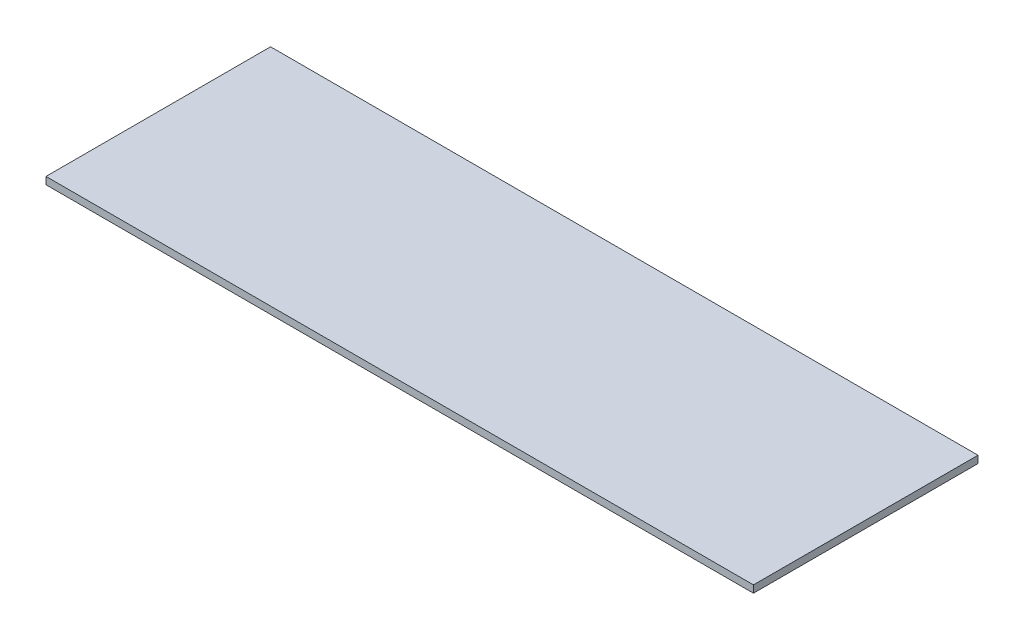
SolidWorks part; units mm, degrees
ref_plane "Front Plane" through (0, 0, 0) normal (0, 0, 1) x (1, 0, 0)
ref_plane "Top Plane" through (0, 0, 0) normal (0, 1, 0) x (1, 0, 0)
ref_plane "Right Plane" through (0, 0, 0) normal (1, 0, 0) x (0, 0, -1)
sketch "Sketch1" plane through (0, 0, 0) normal (0, 1, 0) x (1, 0, 0)
  line L1 (0, 0) -> (293, 0)
  line L2 (0, 0) -> (0, 93)
  line L3 (0, 93) -> (293, 93)
  line L4 (293, 0) -> (293, 93)
  dimension "D1" = 293
  dimension "D2" = 93
extrude "Boss-Extrude1" add sketch "Sketch1" along normal blind 3
